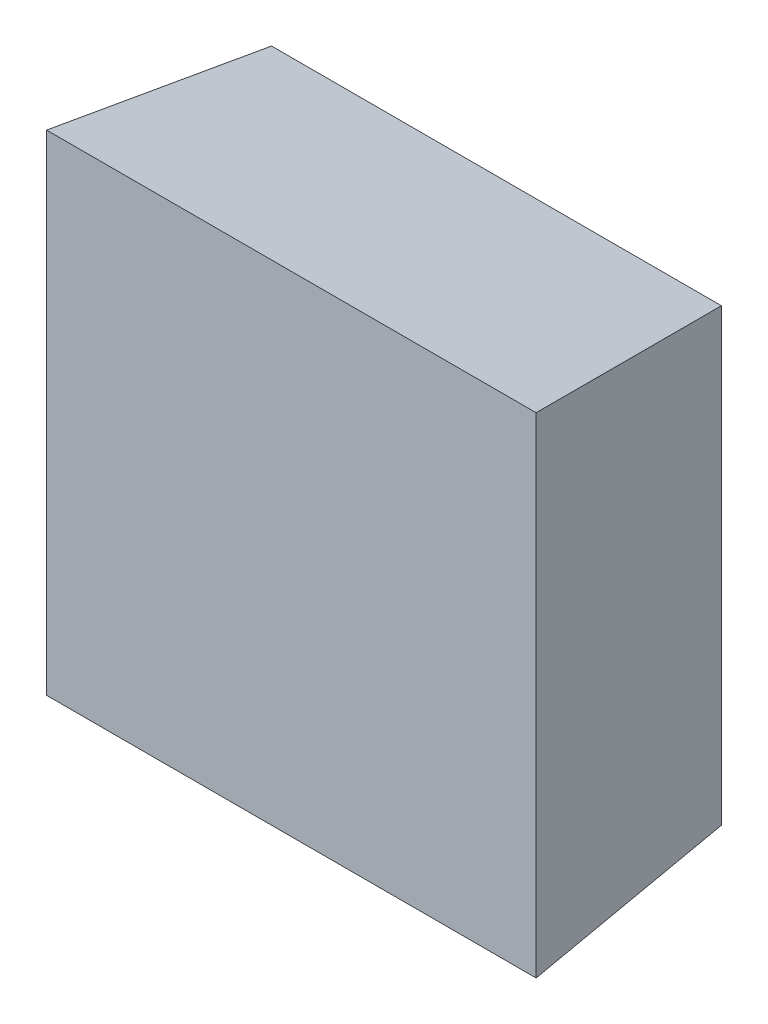
SolidWorks part; units mm, degrees
ref_plane "Front Plane" through (0, 0, 0) normal (0, 0, 1) x (1, 0, 0)
ref_plane "Top Plane" through (0, 0, 0) normal (0, 1, 0) x (1, 0, 0)
ref_plane "Right Plane" through (0, 0, 0) normal (1, 0, 0) x (0, 0, -1)
sketch "Sketch1" plane through (0, 0, 0) normal (0, 0, 1) x (1, 0, 0)
  line L1 (0, 0) -> (40, 0)
  line L2 (0, 0) -> (0, 40)
  line L3 (0, 40) -> (40, 40)
  line L4 (40, 0) -> (40, 40)
extrude "Boss-Extrude1" add sketch "Sketch1" along normal blind 20
draft "Draft1" type of draft neutral plane draft angle 10 faces to draft 2 face at (20, 40, 10) face at (40, 20, 10) neutral plane through (0, 0, 0) neutral plane normal (0, 0, -1) parameters "D1"=10
